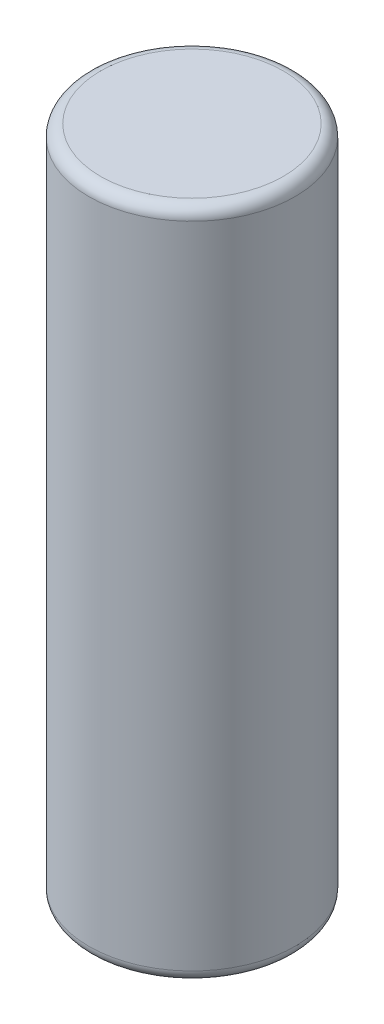
SolidWorks part; units mm, degrees
ref_plane "Front Plane" through (0, 0, 0) normal (0, 0, 1) x (1, 0, 0)
ref_plane "Top Plane" through (0, 0, 0) normal (0, 1, 0) x (1, 0, 0)
ref_plane "Right Plane" through (0, 0, 0) normal (1, 0, 0) x (0, 0, -1)
sketch "Sketch1" plane through (0, 0, 0) normal (0, 1, 0) x (1, 0, 0)
  circle A0 centre (0, 0) radius 14.1
  dimension "D1" = 28.2
extrude "Boss-Extrude1" add sketch "Sketch1" along normal blind 92 contours A0
fillet "Fillet1" radius 1.6 2 edges at (0, 0, 14.1) (0, 92, 14.1)
